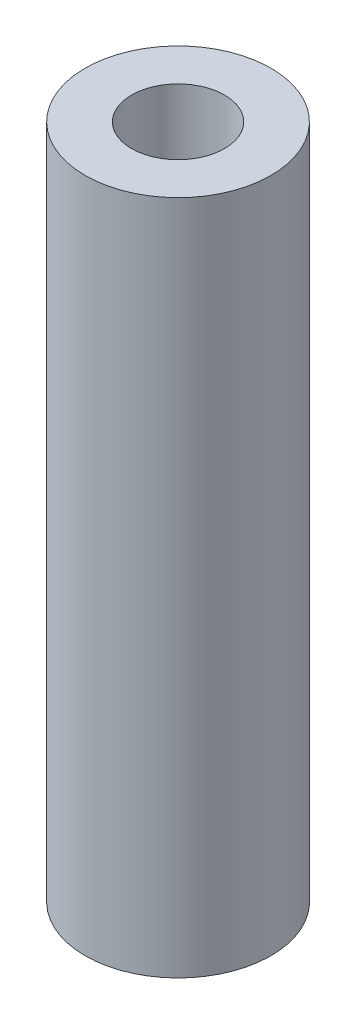
SolidWorks part; units mm, degrees
ref_plane "Front Plane" through (0, 0, 0) normal (1, 0, 0) x (0, 1, 0)
ref_plane "Top Plane" through (0, 0, 0) normal (0, 0, 1) x (0, 1, 0)
ref_plane "Right Plane" through (0, 0, 0) normal (0, 1, 0) x (-1, 0, 0)
sketch "Sketch1" plane through (0, 0, 0) normal (0, 1, 0) x (-1, 0, 0)
  circle A0 centre (0, 0) radius 11
  circle A1 centre (0, 0) radius 5.5
  dimension "D1" = 22
  dimension "D2" = 11
extrude "Boss-Extrude1" add sketch "Sketch1" along normal mid plane 80
